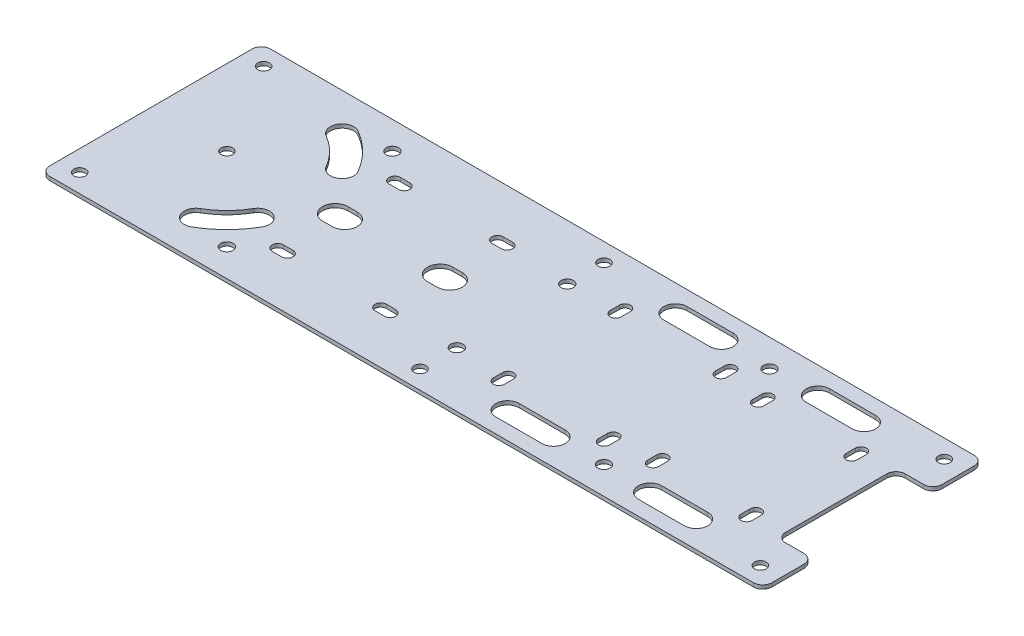
SolidWorks part; units mm, degrees
ref_plane "Front Plane" through (0, 0, 0) normal (0, 0, 1) x (1, 0, 0)
ref_plane "Top Plane" through (0, 0, 0) normal (0, 1, 0) x (1, 0, 0)
ref_plane "Right Plane" through (0, 0, 0) normal (1, 0, 0) x (0, 0, -1)
sketch "Sketch1" plane through (0, 0, 0) normal (0, 1, 0) x (1, 0, 0)
  line L0 (-195, -60) -> (195, -60) construction
  line L1 (-196.27, -60) -> (196.27, -60)
  line L2 (-196.27, -60) -> (-196.27, 60)
  line L3 (-196.27, 60) -> (196.27, 60)
  line L4 (196.27, -60) -> (196.27, 60)
  line L5 (-196.27, -60) -> (196.27, 60) construction
  line L6 (-196.27, 60) -> (196.27, -60) construction
  circle A0 centre (0, -50) radius 3.2 construction
  circle A1 centre (185, -50) radius 3.2 construction
  circle A2 centre (185, 50) radius 3.2 construction
  circle A3 centre (0, 50) radius 3.2 construction
  circle A4 centre (-185, 50) radius 3.2 construction
  circle A5 centre (-185, -50) radius 3.2 construction
  circle A6 centre (0, -50) radius 3.2
  circle A7 centre (185, -50) radius 3.2
  circle A8 centre (185, 50) radius 3.2
  circle A9 centre (0, 50) radius 3.2
  circle A10 centre (-185, 50) radius 3.2
  circle A11 centre (-185, -50) radius 3.2
  circle A12 centre (185, 50) radius 5.7735 construction
  point P0 (0, 0)
  dimension "D1" = 11.27
extrude "Boss-Extrude1" add sketch "Sketch1" along normal blind 2.03
sketch "Sketch2" plane through (0, 0, 0) normal (0, 1, 0) x (1, 0, 0)
  line L0 (0, 0) -> (313.0487, 0) construction
  line L1 (196.27, -60) -> (196.27, 60) construction
  line L2 (181.27, -32.5) -> (196.27, -32.5)
  line L3 (176.27, -27.5) -> (176.27, 27.5)
  line L4 (181.27, 32.5) -> (196.27, 32.5)
  line L5 (196.27, -32.5) -> (196.27, 32.5)
  line L6 (176.27, -32.5) -> (196.27, 32.5) construction
  line L7 (176.27, 32.5) -> (196.27, -32.5) construction
  arc A0 (181.27, -32.5) -> (176.27, -27.5) centre (181.27, -27.5) cw
  arc A1 (176.27, 27.5) -> (181.27, 32.5) centre (181.27, 27.5) cw
  point P3 (186.27, 0)
  dimension "D3" = 5
  dimension "D1" = 20
  dimension "D2" = 65
extrude "Cut-Extrude3" cut sketch "Sketch2" against normal through all and the other way through all
sketch "Sketch3" plane through (0, 0, 0) normal (0, 1, 0) x (1, 0, 0)
  line L0 (-90.375, 34.33) -> (-95.535, 34.33) construction
  line L1 (-95.535, 29.17) -> (-90.375, 29.17) construction
  line L2 (-90.375, 34.33) -> (-95.535, 34.33) construction
  line L3 (-95.535, 29.17) -> (-90.375, 29.17) construction
  line L4 (-39.625, 29.17) -> (-34.465, 29.17) construction
  line L5 (-34.465, 34.33) -> (-39.625, 34.33) construction
  line L6 (-39.625, 29.17) -> (-34.465, 29.17) construction
  line L7 (-34.465, 34.33) -> (-39.625, 34.33) construction
  line L8 (-95.535, -34.33) -> (-90.375, -34.33) construction
  line L9 (-90.375, -29.17) -> (-95.535, -29.17) construction
  line L10 (-95.535, -34.33) -> (-90.375, -34.33) construction
  line L11 (-90.375, -29.17) -> (-95.535, -29.17) construction
  line L12 (-39.625, -34.33) -> (-34.465, -34.33) construction
  line L13 (-34.465, -29.17) -> (-39.625, -29.17) construction
  line L14 (-39.625, -34.33) -> (-34.465, -34.33) construction
  line L15 (-34.465, -29.17) -> (-39.625, -29.17) construction
  line L16 (-90.375, 34.83) -> (-95.535, 34.83)
  line L17 (-95.535, 28.67) -> (-90.375, 28.67)
  line L18 (-39.625, 28.67) -> (-34.465, 28.67)
  line L19 (-34.465, 34.83) -> (-39.625, 34.83)
  line L20 (-95.535, -34.83) -> (-90.375, -34.83)
  line L21 (-90.375, -28.67) -> (-95.535, -28.67)
  line L22 (-39.625, -34.83) -> (-34.465, -34.83)
  line L23 (-34.465, -28.67) -> (-39.625, -28.67)
  line L24 (27.1437, 29.25) -> (27.1437, 34.25) construction
  line L25 (24.1437, 29.25) -> (24.1437, 34.25)
  line L26 (30.1437, 29.25) -> (30.1437, 34.25)
  line L27 (84.2937, 29.25) -> (84.2937, 34.25) construction
  line L28 (81.2937, 29.25) -> (81.2937, 34.25)
  line L29 (87.2937, 29.25) -> (87.2937, 34.25)
  line L30 (27.1437, -34.25) -> (27.1437, -29.25) construction
  line L31 (24.1437, -34.25) -> (24.1437, -29.25)
  line L32 (30.1437, -34.25) -> (30.1437, -29.25)
  line L33 (84.2937, -34.25) -> (84.2937, -29.25) construction
  line L34 (81.2937, -34.25) -> (81.2937, -29.25)
  line L35 (87.2937, -34.25) -> (87.2937, -29.25)
  line L36 (107.7875, 26.075) -> (107.7875, 31.075) construction
  line L37 (104.7875, 26.075) -> (104.7875, 31.075)
  line L38 (110.7875, 26.075) -> (110.7875, 31.075)
  line L39 (158.5875, 26.075) -> (158.5875, 31.075) construction
  line L40 (155.5875, 26.075) -> (155.5875, 31.075)
  line L41 (161.5875, 26.075) -> (161.5875, 31.075)
  line L42 (107.7875, -31.075) -> (107.7875, -26.075) construction
  line L43 (104.7875, -31.075) -> (104.7875, -26.075)
  line L44 (110.7875, -31.075) -> (110.7875, -26.075)
  line L45 (158.5875, -31.075) -> (158.5875, -26.075) construction
  line L46 (155.5875, -31.075) -> (155.5875, -26.075)
  line L47 (161.5875, -31.075) -> (161.5875, -26.075)
  line L48 (120.6875, 45.6375) -> (145.6875, 45.6375) construction
  line L49 (120.6875, 51.9875) -> (145.6875, 51.9875)
  line L50 (120.6875, 39.2875) -> (145.6875, 39.2875)
  line L51 (120.6875, -45.6375) -> (145.6875, -45.6375) construction
  line L52 (120.6875, -39.2875) -> (145.6875, -39.2875)
  line L53 (120.6875, -51.9875) -> (145.6875, -51.9875)
  line L54 (43.2188, -45.6375) -> (68.2188, -45.6375) construction
  line L55 (43.2188, -39.2875) -> (68.2188, -39.2875)
  line L56 (43.2188, -51.9875) -> (68.2188, -51.9875)
  line L57 (43.2188, 45.6375) -> (68.2188, 45.6375) construction
  line L58 (43.2188, 51.9875) -> (68.2188, 51.9875)
  line L59 (43.2188, 39.2875) -> (68.2188, 39.2875)
  line L60 (55.7188, 20.6375) -> (55.7188, 45.6375) construction
  line L61 (32.7, 20.6375) -> (78.7375, 20.6375) construction
  line L62 (133.1875, 17.4625) -> (133.1875, 45.6375) construction
  line L63 (152.2375, 17.4625) -> (114.1375, 17.4625) construction
  line L64 (55.7188, -45.6375) -> (55.7188, -20.6375) construction
  line L65 (32.7, -20.6375) -> (78.7375, -20.6375) construction
  line L66 (133.1875, -45.6375) -> (133.1875, -17.4625) construction
  line L67 (152.2375, -17.4625) -> (114.1375, -17.4625) construction
  line L68 (-155, 0) -> (-102.8, 0) construction
  line L69 (-132.075, 39.7073) -> (-155, 0) construction
  line L70 (-155, 0) -> (-118.089, 36.911) construction
  line L71 (-96.105, 0) -> (-90.945, 0) construction
  line L72 (-96.105, 6.85) -> (-90.945, 6.85)
  line L73 (-96.105, -6.85) -> (-90.945, -6.85)
  line L74 (-33.895, 0) -> (-39.055, 0) construction
  line L75 (-33.895, -6.85) -> (-39.055, -6.85)
  line L76 (-33.895, 6.85) -> (-39.055, 6.85)
  arc A0 (-95.535, 34.33) -> (-95.535, 29.17) centre (-95.535, 31.75) ccw construction
  arc A1 (-90.375, 29.17) -> (-90.375, 34.33) centre (-90.375, 31.75) ccw construction
  arc A2 (-95.535, 34.33) -> (-95.535, 29.17) centre (-95.535, 31.75) ccw construction
  arc A3 (-90.375, 29.17) -> (-90.375, 34.33) centre (-90.375, 31.75) ccw construction
  arc A4 (-39.625, 34.33) -> (-39.625, 29.17) centre (-39.625, 31.75) ccw construction
  arc A5 (-34.465, 29.17) -> (-34.465, 34.33) centre (-34.465, 31.75) ccw construction
  arc A6 (-39.625, 34.33) -> (-39.625, 29.17) centre (-39.625, 31.75) ccw construction
  arc A7 (-34.465, 29.17) -> (-34.465, 34.33) centre (-34.465, 31.75) ccw construction
  arc A8 (-95.535, -29.17) -> (-95.535, -34.33) centre (-95.535, -31.75) ccw construction
  arc A9 (-90.375, -34.33) -> (-90.375, -29.17) centre (-90.375, -31.75) ccw construction
  arc A10 (-95.535, -29.17) -> (-95.535, -34.33) centre (-95.535, -31.75) ccw construction
  arc A11 (-90.375, -34.33) -> (-90.375, -29.17) centre (-90.375, -31.75) ccw construction
  arc A12 (-39.625, -29.17) -> (-39.625, -34.33) centre (-39.625, -31.75) ccw construction
  arc A13 (-34.465, -34.33) -> (-34.465, -29.17) centre (-34.465, -31.75) ccw construction
  arc A14 (-39.625, -29.17) -> (-39.625, -34.33) centre (-39.625, -31.75) ccw construction
  arc A15 (-34.465, -34.33) -> (-34.465, -29.17) centre (-34.465, -31.75) ccw construction
  circle A16 centre (-93.525, 0) radius 6.35 construction
  circle A17 centre (-93.525, 0) radius 6.35 construction
  circle A18 centre (-36.475, 0) radius 6.35 construction
  circle A19 centre (-36.475, 0) radius 6.35 construction
  arc A20 (-95.535, 34.83) -> (-95.535, 28.67) centre (-95.535, 31.75) ccw
  arc A21 (-90.375, 28.67) -> (-90.375, 34.83) centre (-90.375, 31.75) ccw
  arc A22 (-34.465, 28.67) -> (-34.465, 34.83) centre (-34.465, 31.75) ccw
  arc A23 (-39.625, 34.83) -> (-39.625, 28.67) centre (-39.625, 31.75) ccw
  arc A24 (-90.375, -34.83) -> (-90.375, -28.67) centre (-90.375, -31.75) ccw
  arc A25 (-95.535, -28.67) -> (-95.535, -34.83) centre (-95.535, -31.75) ccw
  arc A26 (-34.465, -34.83) -> (-34.465, -28.67) centre (-34.465, -31.75) ccw
  arc A27 (-39.625, -28.67) -> (-39.625, -34.83) centre (-39.625, -31.75) ccw
  circle A28 centre (-93.525, 0) radius 6.85 construction
  circle A29 centre (-36.475, 0) radius 6.85 construction
  circle A30 centre (84.2937, -31.75) radius 2.5797 construction
  circle A31 centre (84.2937, 31.75) radius 2.5797 construction
  circle A32 centre (27.1437, 31.75) radius 2.5797 construction
  circle A33 centre (27.1437, -31.75) radius 2.5797 construction
  circle A34 centre (84.2937, -31.75) radius 2.5797 construction
  circle A35 centre (84.2937, 31.75) radius 2.5797 construction
  circle A36 centre (27.1437, 31.75) radius 2.5797 construction
  circle A37 centre (27.1437, -31.75) radius 2.5797 construction
  arc A38 (24.1437, 29.25) -> (30.1437, 29.25) centre (27.1437, 29.25) ccw
  arc A39 (30.1437, 34.25) -> (24.1437, 34.25) centre (27.1437, 34.25) ccw
  arc A40 (81.2937, 29.25) -> (87.2937, 29.25) centre (84.2937, 29.25) ccw
  arc A41 (87.2937, 34.25) -> (81.2937, 34.25) centre (84.2937, 34.25) ccw
  arc A42 (24.1437, -34.25) -> (30.1437, -34.25) centre (27.1437, -34.25) ccw
  arc A43 (30.1437, -29.25) -> (24.1437, -29.25) centre (27.1437, -29.25) ccw
  arc A44 (81.2937, -34.25) -> (87.2937, -34.25) centre (84.2937, -34.25) ccw
  arc A45 (87.2937, -29.25) -> (81.2937, -29.25) centre (84.2937, -29.25) ccw
  circle A46 centre (107.7875, -28.575) radius 2.5797 construction
  circle A47 centre (158.5875, -28.575) radius 2.5797 construction
  circle A48 centre (158.5875, 28.575) radius 2.5797 construction
  circle A49 centre (107.7875, 28.575) radius 2.5797 construction
  circle A50 centre (107.7875, -28.575) radius 2.5797 construction
  circle A51 centre (158.5875, -28.575) radius 2.5797 construction
  circle A52 centre (158.5875, 28.575) radius 2.5797 construction
  circle A53 centre (107.7875, 28.575) radius 2.5797 construction
  arc A54 (104.7875, 26.075) -> (110.7875, 26.075) centre (107.7875, 26.075) ccw
  arc A55 (110.7875, 31.075) -> (104.7875, 31.075) centre (107.7875, 31.075) ccw
  arc A56 (155.5875, 26.075) -> (161.5875, 26.075) centre (158.5875, 26.075) ccw
  arc A57 (161.5875, 31.075) -> (155.5875, 31.075) centre (158.5875, 31.075) ccw
  arc A58 (104.7875, -31.075) -> (110.7875, -31.075) centre (107.7875, -31.075) ccw
  arc A59 (110.7875, -26.075) -> (104.7875, -26.075) centre (107.7875, -26.075) ccw
  arc A60 (155.5875, -31.075) -> (161.5875, -31.075) centre (158.5875, -31.075) ccw
  arc A61 (161.5875, -26.075) -> (155.5875, -26.075) centre (158.5875, -26.075) ccw
  arc A62 (120.6875, 51.9875) -> (120.6875, 39.2875) centre (120.6875, 45.6375) ccw
  arc A63 (145.6875, 39.2875) -> (145.6875, 51.9875) centre (145.6875, 45.6375) ccw
  arc A64 (120.6875, -39.2875) -> (120.6875, -51.9875) centre (120.6875, -45.6375) ccw
  arc A65 (145.6875, -51.9875) -> (145.6875, -39.2875) centre (145.6875, -45.6375) ccw
  arc A66 (43.2188, -39.2875) -> (43.2188, -51.9875) centre (43.2188, -45.6375) ccw
  arc A67 (68.2188, -51.9875) -> (68.2188, -39.2875) centre (68.2188, -45.6375) ccw
  arc A68 (43.2188, 51.9875) -> (43.2188, 39.2875) centre (43.2188, 45.6375) ccw
  arc A69 (68.2188, 39.2875) -> (68.2188, 51.9875) centre (68.2188, 45.6375) ccw
  circle A70 centre (-155, 0) radius 3.15
  circle A71 centre (-155, 0) radius 37 construction
  circle A72 centre (-155, 0) radius 37 construction
  arc A73 (-135.25, -34.208) -> (-120.792, -19.75) centre (-155, 0) ccw
  arc A74 (-128.9, -45.2065) -> (-109.7935, -26.1) centre (-155, 0) ccw
  arc A75 (-128.9, 45.2065) -> (-135.25, 34.208) centre (-132.075, 39.7073) ccw
  arc A76 (-109.7935, 26.1) -> (-120.792, 19.75) centre (-115.2927, 22.925) cw
  arc A77 (-109.7935, -26.1) -> (-120.792, -19.75) centre (-115.2927, -22.925) ccw
  arc A78 (-128.9, -45.2065) -> (-135.25, -34.208) centre (-132.075, -39.7073) cw
  arc A79 (-128.9, 45.2065) -> (-128.9, -45.2065) centre (-155, 0) ccw construction
  arc A80 (-109.7935, 26.1) -> (-128.9, 45.2065) centre (-155, 0) ccw
  arc A81 (-135.25, 34.208) -> (-135.25, -34.208) centre (-155, 0) ccw construction
  circle A82 centre (-155, 0) radius 39.5 construction
  arc A83 (-109.7935, -26.1) -> (-102.8, 0) centre (-155, 0) ccw construction
  arc A84 (-120.792, 19.75) -> (-135.25, 34.208) centre (-155, 0) ccw
  arc A85 (-120.792, -19.75) -> (-115.5, 0) centre (-155, 0) ccw construction
  arc A86 (-115.5, 0) -> (-120.792, 19.75) centre (-155, 0) ccw construction
  arc A87 (-102.8, 0) -> (-109.7935, 26.1) centre (-155, 0) ccw construction
  arc A88 (-96.105, 6.85) -> (-96.105, -6.85) centre (-96.105, 0) ccw
  arc A89 (-90.945, -6.85) -> (-90.945, 6.85) centre (-90.945, 0) ccw
  arc A90 (-33.895, -6.85) -> (-33.895, 6.85) centre (-33.895, 0) ccw
  arc A91 (-39.055, 6.85) -> (-39.055, -6.85) centre (-39.055, 0) ccw
  point P72 (27.1437, 31.75)
  point P78 (84.2937, 31.75)
  point P85 (27.1437, -31.75)
  point P92 (84.2937, -31.75)
  point P112 (107.7875, 28.575)
  point P119 (158.5875, 28.575)
  point P126 (107.7875, -28.575)
  point P133 (158.5875, -28.575)
  point P140 (133.1875, 45.6375)
  point P146 (133.1875, -45.6375)
  point P153 (55.7188, -45.6375)
  point P160 (55.7188, 45.6375)
  point P189 (-115.5, 0)
  point P207 (-93.525, 0)
  point P214 (-36.475, 0)
  dimension "D9" = 6.3
  dimension "D2" = 6
  dimension "D3" = 5
  dimension "D4" = 6
  dimension "D5" = 5
  dimension "D6" = 25
  dimension "D7" = 25
  dimension "D8" = 12.7
  dimension "D11" = 12.7
  dimension "D12" = 60
  dimension "D13" = 15
  dimension "D14" = 5.16
  dimension "D15" = 5.16
  dimension "D1" = 0.5
  dimension "D10" = 2.5
extrude "Cut-Extrude4" cut sketch "Sketch3" along normal through all
fillet "Fillet1" radius 5 6 edges at (196.27, 1.015, 32.5) (196.27, 1.015, -32.5) (-196.27, 1.015, 60) (-196.27, 1.015, -60) (196.27, 1.015, -60) (196.27, 1.015, 60)
sketch "Sketch4" plane through (0, 2.03, 0) normal (0, 1, 0) x (1, 0, 0)
  line L0 (0, 0) -> (226.4213, 0) construction
  circle A0 centre (-110, 45) radius 3.35
  circle A1 centre (0, 30) radius 3.35
  circle A2 centre (95, 45) radius 3.35
  circle A3 centre (95, -45) radius 3.35
  circle A4 centre (0, -30) radius 3.35
  circle A5 centre (-110, -45) radius 3.35
  dimension "D3" = 6.7
  dimension "D1" = 45
  dimension "D2" = 95
  dimension "D4" = 110
  dimension "D5" = 30
extrude "Cut-Extrude5" cut sketch "Sketch4" against normal through all
equation "\"D15@Sketch3\"=\"D14@Sketch3\""
